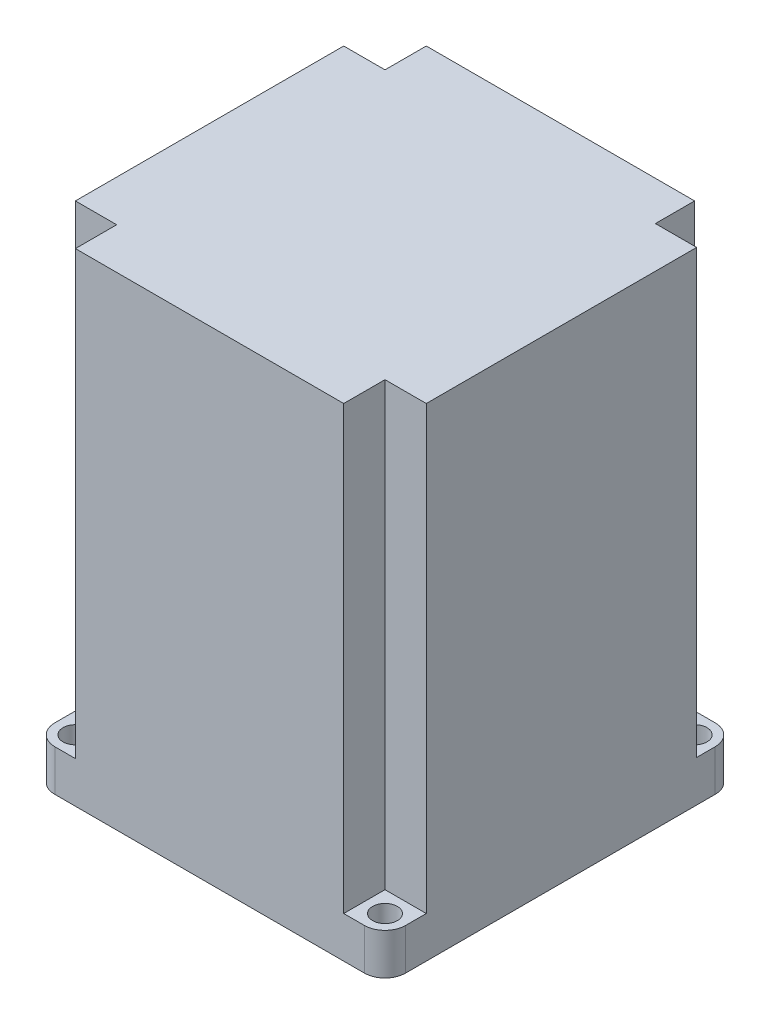
SolidWorks part; units mm, degrees
ref_plane "Alzado" through (0, 0, 0) normal (0, 0, 1) x (1, 0, 0)
ref_plane "Planta" through (0, 0, 0) normal (0, 1, 0) x (1, 0, 0)
ref_plane "Vista lateral" through (0, 0, 0) normal (1, 0, 0) x (0, 0, -1)
sketch "Croquis1" plane through (0, 0, 0) normal (0, 1, 0) x (1, 0, 0)
  line L1 (-42.5, 42.5) -> (42.5, 42.5)
  line L2 (-42.5, 42.5) -> (-42.5, -42.5)
  line L3 (-42.5, -42.5) -> (42.5, -42.5)
  line L4 (42.5, 42.5) -> (42.5, -42.5)
  line L5 (-42.5, 42.5) -> (42.5, -42.5) construction
  line L6 (-42.5, -42.5) -> (42.5, 42.5) construction
  point P0 (0, 0)
  dimension "D1" = 85
  dimension "D2" = 85
extrude "Saliente-Extruir1" add sketch "Croquis1" along normal blind 117
sketch "Croquis2" plane through (0, 117, 0) normal (0, 1, 0) x (1, 0, 0)
  line L0 (-42.5, 42.5) -> (-32.5, 42.5)
  line L1 (42.5, 42.5) -> (-42.5, 42.5) construction
  line L2 (-32.5, 42.5) -> (-32.5, 32.5)
  line L3 (42.5, 42.5) -> (32.5, 42.5)
  line L4 (32.5, 42.5) -> (32.5, 33)
  line L5 (32.5, 33) -> (42.5, 33)
  line L6 (42.5, -42.5) -> (42.5, 42.5) construction
  line L7 (42.5, 33) -> (42.5, 42.5)
  line L8 (-32.5, 32.5) -> (-42.5, 32.5)
  line L9 (-42.5, 42.5) -> (-42.5, -42.5) construction
  line L10 (-42.5, 32.5) -> (-42.5, 42.5)
  line L11 (-42.5, -42.5) -> (-32.5, -42.5)
  line L12 (-42.5, -42.5) -> (42.5, -42.5) construction
  line L13 (-32.5, -42.5) -> (-32.5, -32.5)
  line L14 (-32.5, -32.5) -> (-42.5, -32.5)
  line L15 (-42.5, -32.5) -> (-42.5, -42.5)
  line L16 (42.5, -42.5) -> (32.5, -42.5)
  line L17 (32.5, -42.5) -> (32.5, -32.5)
  line L18 (32.5, -32.5) -> (42.5, -32.5)
  line L19 (42.5, -32.5) -> (42.5, -42.5)
  dimension "D1" = 10
  dimension "D2" = 10
  dimension "D3" = 10
  dimension "D4" = 10
  dimension "D5" = 10
  dimension "D6" = 10
  dimension "D7" = 10
extrude "Cortar-Extruir1" cut sketch "Croquis2" against normal blind 117 from offset 10
sketch "Croquis3" plane through (0, 0, 0) normal (0, -1, 0) x (1, 0, 0)
  circle A0 centre (0, 0) radius 31
  dimension "D1" = 62
extrude "Cortar-Extruir2" cut sketch "Croquis3" against normal blind 2
sketch "Croquis4" plane through (0, 2, 0) normal (0, -1, 0) x (1, 0, 0)
  circle A0 centre (0, 0) radius 8
  dimension "D1" = 16
extrude "Saliente-Extruir2" add sketch "Croquis4" along normal blind 36
sketch "Croquis7" plane through (0, 0, 0) normal (0, -1, 0) x (1, 0, 0)
  line L0 (-42.5, 42.5) -> (-32.5, 42.5)
  line L1 (-32.5, 42.5) -> (-32.5, 32.5)
  line L2 (-42.5, 42.5) -> (-42.5, 32.5)
  line L3 (-42.5, -42.5) -> (-42.5, 42.5) construction
  line L4 (-42.5, 32.5) -> (-32.5, 32.5)
  line L5 (42.5, 42.5) -> (32.5, 42.5)
  line L6 (-42.5, 42.5) -> (42.5, 42.5) construction
  line L7 (32.5, 42.5) -> (32.5, 32.5)
  line L8 (32.5, 32.5) -> (42.5, 32.5)
  line L9 (42.5, 42.5) -> (42.5, -42.5) construction
  line L10 (42.5, 32.5) -> (42.5, 42.5)
  line L11 (-42.5, -42.5) -> (-42.5, -32.5)
  line L12 (-42.5, -32.5) -> (-32.5, -32.5)
  line L13 (-32.5, -32.5) -> (-32.5, -42.5)
  line L14 (42.5, -42.5) -> (-42.5, -42.5) construction
  line L15 (-32.5, -42.5) -> (-42.5, -42.5)
  line L16 (42.5, -42.5) -> (32.5, -42.5)
  line L17 (32.5, -42.5) -> (32.5, -32.5)
  line L18 (32.5, -32.5) -> (42.5, -32.5)
  line L19 (42.5, -32.5) -> (42.5, -42.5)
  circle A0 centre (37.5, -37.5) radius 3
  circle A1 centre (-37.5, -37.5) radius 3
  circle A2 centre (-37.5, 37.5) radius 3
  circle A3 centre (37.5, 37.5) radius 3
  dimension "D9" = 6
  dimension "D10" = 6
  dimension "D11" = 6
  dimension "D12" = 6
  dimension "D1" = 10
  dimension "D2" = 10
  dimension "D3" = 10
  dimension "D4" = 10
  dimension "D5" = 10
  dimension "D6" = 10
  dimension "D7" = 10
  dimension "D8" = 10
extrude "Cortar-Extruir3" cut sketch "Croquis7" against normal up to surface (10 mm away) contours A2 | A3 | A1 | A0 up to face at (-37.5, 10, -37.5)
fillet "Redondeo7" radius 5 4 edges at (-42.5, 5, -42.5) (42.5, 5, -42.5) (42.5, 5, 42.5) (-42.5, 5, 42.5)
